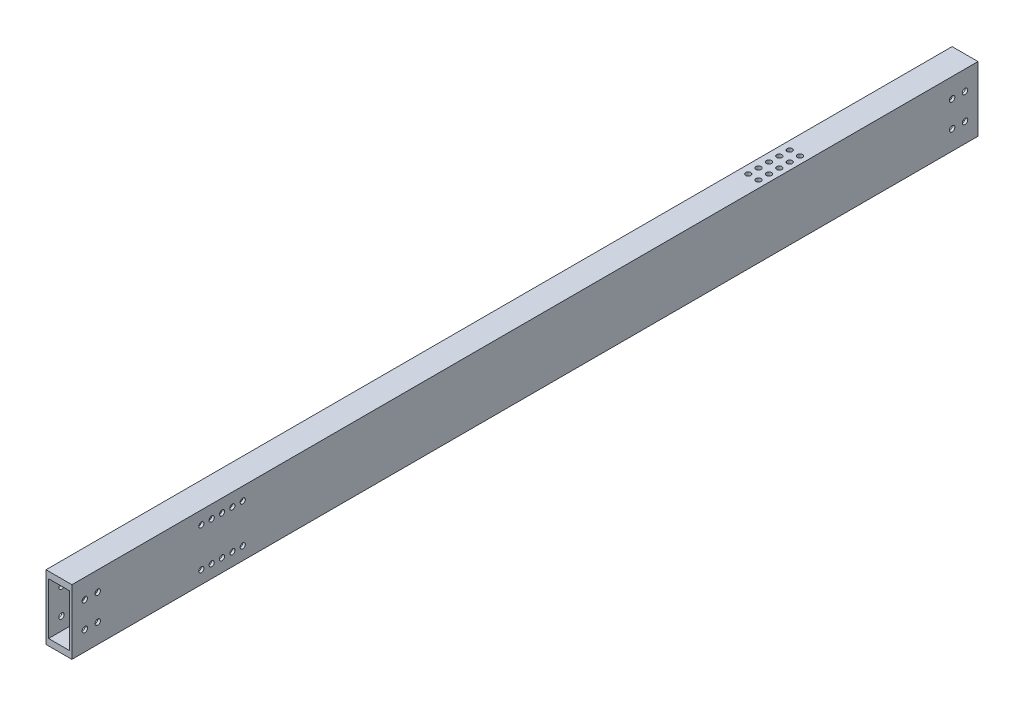
SolidWorks part; units mm, degrees
material "1060 合金"
ref_plane "前视基准面" through (0, 0, 0) normal (0, 0, 1) x (1, 0, 0)
ref_plane "上视基准面" through (0, 0, 0) normal (0, 1, 0) x (1, 0, 0)
ref_plane "右视基准面" through (0, 0, 0) normal (1, 0, 0) x (0, 0, -1)
sketch "草图1" plane through (0, 0, 0) normal (0, 0, 1) x (1, 0, 0)
  line L1 (-10, -25) -> (10, -25)
  line L2 (-10, -25) -> (-10, 25)
  line L3 (-10, 25) -> (10, 25)
  line L4 (10, -25) -> (10, 25)
  line L5 (-10, -25) -> (10, 25) construction
  line L6 (-10, 25) -> (10, -25) construction
  line L7 (-8, -20) -> (8, -20)
  line L8 (-8, -20) -> (-8, 20)
  line L9 (-8, 20) -> (8, 20)
  line L10 (8, -20) -> (8, 20)
  line L11 (-8, -20) -> (8, 20) construction
  line L12 (-8, 20) -> (8, -20) construction
  point P0 (0, 0)
  point P6 (0, 0)
  dimension "D1" = 50
  dimension "D2" = 20
  dimension "D3" = 2
extrude "凸台-拉伸1" add sketch "草图1" along normal blind 700
ref_plane "基准面1" through (-40, 280, 280) normal (0, 0, -1) x (0, -1, 0)
sketch "草图5" plane through (-10, 0, 0) normal (-1, 0, 0) x (0, 0, 1)
  circle A1 centre (10, 10) radius 2.1
  circle A2 centre (20, 10) radius 2.1
  circle A3 centre (10, -10) radius 2.1
  circle A4 centre (20, -10) radius 2.1
  point P0 (0, 0)
  point P1 (10, 0)
  point P3 (20, 0)
  point P6 (10, 10)
  point P7 (10, -10)
  point P8 (20, 10)
  point P9 (20, -10)
  dimension "D7" = 4.2
  dimension "D8" = 4.2
  dimension "D9" = 4.2
  dimension "D10" = 4.2
  dimension "D1" = 10
  dimension "D2" = 10
  dimension "D3" = 10
  dimension "D4" = 10
  dimension "D5" = 10
  dimension "D6" = 10
extrude "切除-拉伸1" cut sketch "草图5" against normal through all
ref_plane "基准面2" through (-40, 280, 350) normal (0, 0, -1) x (0, -1, 0)
mirror "镜向1" about plane through (-40, 280, 350) normal (0, 0, -1) of "切除-拉伸1"
sketch "草图6" plane through (0, -25, 0) normal (0, -1, 0) x (1, 0, 0)
  line L0 (4.5, 132) -> (10, 132) construction
  line L2 (10, 700) -> (10, 0) construction
  line L3 (10, 132) -> (10, 0) construction
  circle A0 centre (-3.5, 132) radius 2
  circle A1 centre (4.5, 132) radius 2
  circle A2 centre (4.5, 140) radius 2
  circle A3 centre (4.5, 148) radius 2
  circle A4 centre (4.5, 156) radius 2
  circle A5 centre (4.5, 164) radius 2
  circle A6 centre (-3.5, 140) radius 2
  circle A7 centre (-3.5, 148) radius 2
  circle A8 centre (-3.5, 156) radius 2
  circle A9 centre (-3.5, 164) radius 2
  dimension "D3" = 4
  dimension "D6" = 32
  dimension "D1" = 132
  dimension "D2" = 5.5
  dimension "D7" = 8
  dimension "D4" = 2
  dimension "D5" = 5
extrude "切除-拉伸3" cut sketch "草图6" against normal through all
sketch "草图7" plane through (-10, 0, 0) normal (-1, 0, 0) x (0, 0, 1)
  line L0 (700, 25) -> (600, 25) construction
  line L1 (700, 25) -> (0, 25) construction
  line L2 (600, 25) -> (600, 15) construction
  line L3 (700, 0) -> (657.2715, 0) construction
  line L4 (700, 25) -> (700, -25) construction
  circle A0 centre (600, 15) radius 2
  circle A1 centre (592, 15) radius 2
  circle A2 centre (584, 15) radius 2
  circle A3 centre (576, 15) radius 2
  circle A4 centre (568, 15) radius 2
  circle A5 centre (592, -15) radius 2
  circle A6 centre (584, -15) radius 2
  circle A7 centre (576, -15) radius 2
  circle A8 centre (568, -15) radius 2
  circle A9 centre (600, -15) radius 2
  dimension "D3" = 4
  dimension "D4" = 5
  dimension "D1" = 100
  dimension "D2" = 10
extrude "切除-拉伸5" cut sketch "草图7" against normal through all
